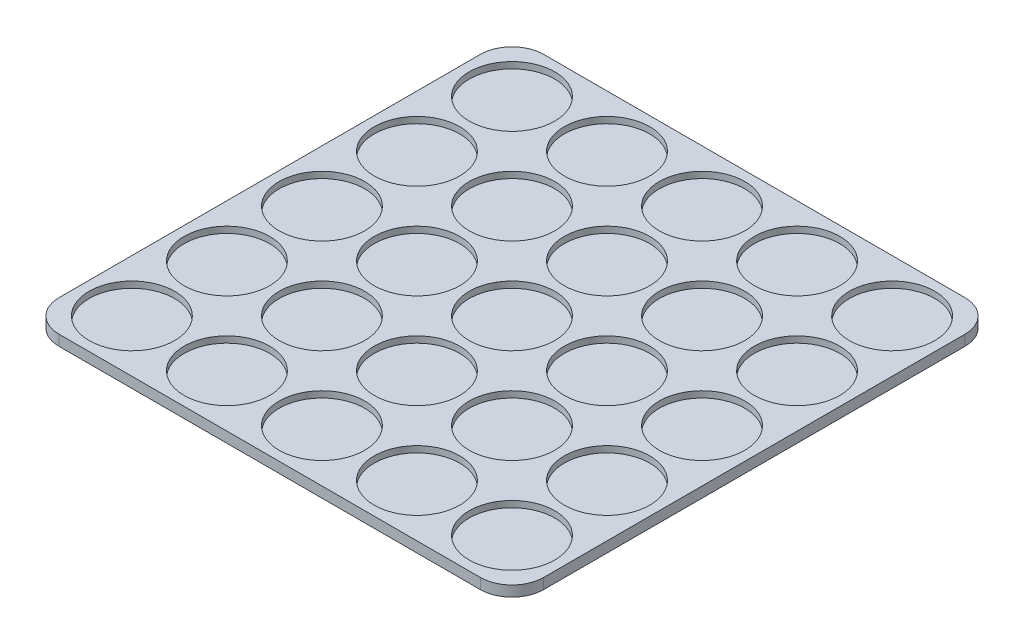
SolidWorks part; units mm, degrees
ref_plane "Front Plane" through (0, 0, 0) normal (0, 0, 1) x (1, 0, 0)
ref_plane "Top Plane" through (0, 0, 0) normal (0, 1, 0) x (1, 0, 0)
ref_plane "Right Plane" through (0, 0, 0) normal (1, 0, 0) x (0, 0, -1)
sketch "Sketch1" plane through (0, 0, 0) normal (0, 1, 0) x (1, 0, 0)
  line L1 (-114.75, 114.75) -> (114.75, 114.75)
  line L2 (-114.75, 114.75) -> (-114.75, -114.75)
  line L3 (-114.75, -114.75) -> (114.75, -114.75)
  line L4 (114.75, 114.75) -> (114.75, -114.75)
  line L5 (-114.75, 114.75) -> (114.75, -114.75) construction
  line L6 (-114.75, -114.75) -> (114.75, 114.75) construction
  point P0 (0, 0)
  dimension "D1" = 229.5
extrude "Boss-Extrude1" add sketch "Sketch1" along normal blind 5
sketch "Sketch2" plane through (0, 5, 0) normal (0, 1, 0) x (1, 0, 0)
  line L0 (-114.75, 114.75) -> (-114.75, -114.75) construction
  line L1 (114.75, 114.75) -> (-114.75, 114.75) construction
  circle A1 centre (-90, 90) radius 20.25
  circle A2 centre (-45, 90) radius 20.25
  circle A3 centre (0, 90) radius 20.25
  circle A4 centre (45, 90) radius 20.25
  circle A5 centre (90, 90) radius 20.25
  circle A6 centre (-45, 45) radius 20.25
  circle A7 centre (0, 45) radius 20.25
  circle A8 centre (45, 45) radius 20.25
  circle A9 centre (90, 45) radius 20.25
  circle A10 centre (-45, 0) radius 20.25
  circle A11 centre (0, 0) radius 20.25
  circle A12 centre (45, 0) radius 20.25
  circle A13 centre (90, 0) radius 20.25
  circle A14 centre (-45, -45) radius 20.25
  circle A15 centre (0, -45) radius 20.25
  circle A16 centre (45, -45) radius 20.25
  circle A17 centre (90, -45) radius 20.25
  circle A18 centre (-45, -90) radius 20.25
  circle A19 centre (0, -90) radius 20.25
  circle A20 centre (45, -90) radius 20.25
  circle A21 centre (90, -90) radius 20.25
  circle A22 centre (-90, 45) radius 20.25
  circle A23 centre (-90, 0) radius 20.25
  circle A24 centre (-90, -45) radius 20.25
  circle A25 centre (-90, -90) radius 20.25
  dimension "D1" = 40.5
  dimension "D2" = 4.5
  dimension "D3" = 4.5
  dimension "D4" = 5
  dimension "D5" = 5
extrude "Cut-Extrude1" cut sketch "Sketch2" against normal blind 3
fillet "Fillet1" radius 15 4 edges at (-114.75, 2.5, -114.75) (114.75, 2.5, -114.75) (114.75, 2.5, 114.75) (-114.75, 2.5, 114.75)
